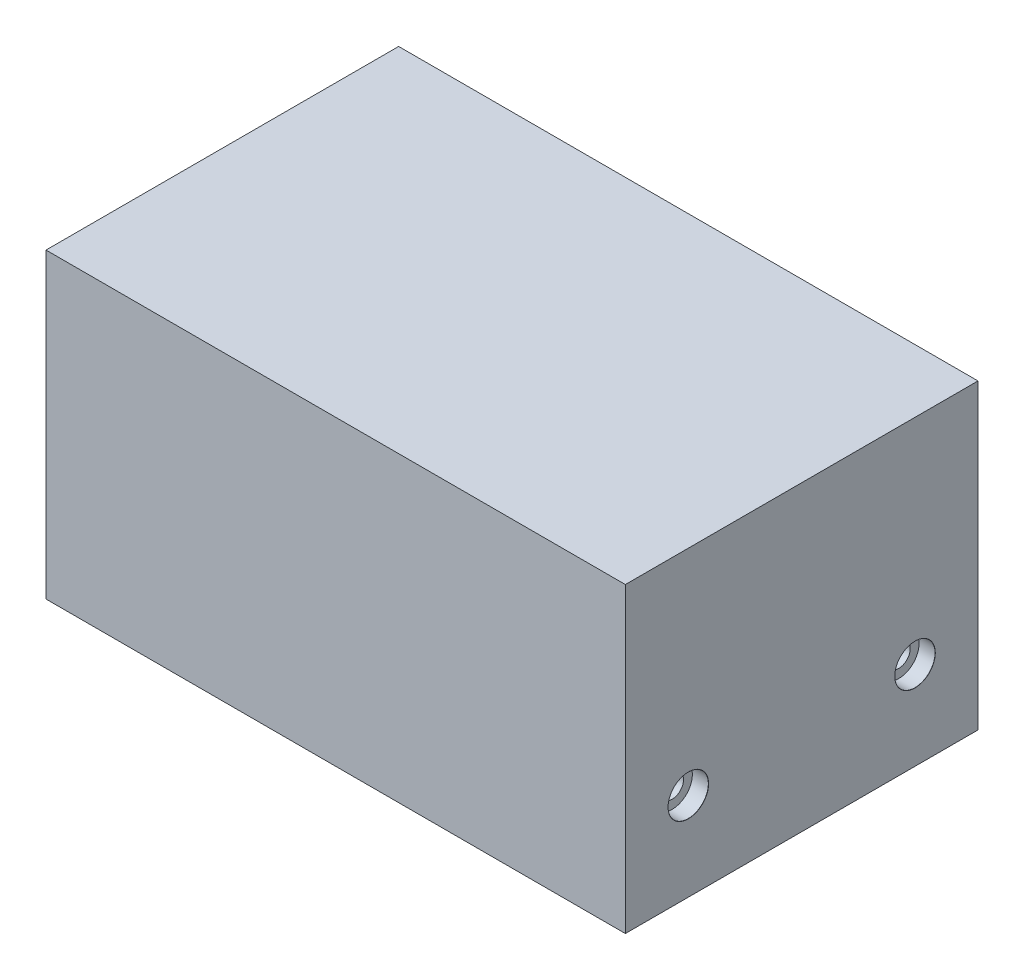
SolidWorks part; units mm, degrees
ref_plane "Alzado" through (0, 0, 0) normal (0, 0, 1) x (1, 0, 0)
ref_plane "Planta" through (0, 0, 0) normal (0, 1, 0) x (1, 0, 0)
ref_plane "Vista lateral" through (0, 0, 0) normal (1, 0, 0) x (0, 0, -1)
sketch "Croquis1" plane through (0, 0, 0) normal (0, 1, 0) x (1, 0, 0)
  line L1 (0, 0) -> (115, 0)
  line L2 (0, 0) -> (0, 70)
  line L3 (0, 70) -> (115, 70)
  line L4 (115, 0) -> (115, 70)
  dimension "D1" = 115
  dimension "D2" = 70
extrude "Saliente-Extruir1" add sketch "Croquis1" along normal blind 5
sketch "Croquis2" plane through (0, 5, 0) normal (0, 1, 0) x (1, 0, 0)
  line L0 (0, 0) -> (115, 0)
  line L1 (115, 0) -> (115, 70)
  line L2 (115, 70) -> (0, 70)
  line L3 (0, 70) -> (0, 65)
  line L4 (0, 70) -> (0, 0) construction
  line L5 (0, 65) -> (110, 65)
  line L6 (110, 65) -> (110, 5)
  line L7 (110, 5) -> (0, 5)
  line L8 (0, 5) -> (0, 0)
  dimension "D1" = 5
  dimension "D2" = 5
  dimension "D3" = 5
extrude "Saliente-Extruir2" add sketch "Croquis2" along normal blind 55
sketch "Croquis3" plane through (110, 0, 0) normal (-1, 0, 0) x (0, 0, 1)
  line L0 (-65, 60) -> (-65, 55)
  line L1 (-65, 60) -> (-65, 5) construction
  line L2 (-65, 55) -> (-5, 55)
  line L3 (-5, 60) -> (-5, 5) construction
  line L4 (-5, 55) -> (-5, 60)
  line L5 (-5, 60) -> (-65, 60)
  dimension "D1" = 5
extrude "Saliente-Extruir3" add sketch "Croquis3" along normal blind 110
sketch "Croquis4" plane through (110, 0, 0) normal (-1, 0, 0) x (0, 0, 1)
  line L0 (-65, 5) -> (-65, 10) construction
  line L1 (-65, 55) -> (-65, 5) construction
  line L2 (-5, 55) -> (-5, 5) construction
  line L3 (-65, 10) -> (-50, 10)
  line L4 (-65, 10) -> (-65, 25)
  line L5 (-65, 25) -> (-50, 25)
  line L6 (-50, 10) -> (-50, 25)
  line L7 (-5, 10) -> (-20, 10)
  line L8 (-5, 10) -> (-5, 25)
  line L9 (-5, 25) -> (-20, 25)
  line L10 (-20, 10) -> (-20, 25)
  line L11 (-65, 5) -> (-5, 5) construction
  dimension "D1" = 5
  dimension "D2" = 15
  dimension "D3" = 15
  dimension "D4" = 15
  dimension "D5" = 15
  dimension "D6" = 5
extrude "Saliente-Extruir4" add sketch "Croquis4" along normal blind 5
sketch "Croquis5" plane through (115, 0, 0) normal (1, 0, 0) x (0, 0, -1)
  line L0 (0, 0) -> (0, 17.5) construction
  line L1 (0, 60) -> (0, 0) construction
  line L2 (0, 17.5) -> (70, 17.5) construction
  line L3 (70, 60) -> (70, 0) construction
  line L4 (0, 17.5) -> (12.5, 17.5) construction
  point P5 (57.5, 17.5)
  point P10 (12.5, 17.5)
  dimension "D1" = 17.5
  dimension "D2" = 12.5
  dimension "D3" = 12.5
hole_wizard "Refrentado para tornillo con cabeza hueca de M41" positions "Croquis6" profile "Croquis7" counterbore size "M4" standard "DIN"
sketch "Croquis6" plane through (115, 0, 0) normal (1, 0, 0) x (0, 0, -1)
  point P0 (12.5, 17.5)
  point P3 (57.5, 17.5)
sketch "Croquis7" plane through (115, 17.5, -12.5) normal (0, 1, 0) x (0, 0, -1)
  line L0 (0, 0) -> (0, 21.8519)
  line L1 (0, 21.8519) -> (2.25, 20.5)
  line L2 (2.25, 20.5) -> (2.25, 3.2)
  line L3 (2.25, 3.2) -> (4, 3.2)
  line L5 (4, 3.2) -> (4, 0.025)
  line L6 (4, 0.025) -> (4.025, 0)
  line L7 (4.025, 0) -> (0, 0)
  line L8 (-4, 0.025) -> (-4.025, 0) construction
  line L10 (0, 21.8519) -> (-2.25, 20.5) construction
  line L11 (0, -6.35) -> (0, 107.95) construction
  dimension "Diámetro de taladro" = 4.5
  dimension "Profundidad de taladro" = 20.5
  dimension "Diámetro de refrentado" = 8
  dimension "Profundidad de refrentado" = 3.2
  dimension "Diámetro de avellanado cercano" = 8.05
  dimension "Ángulo de avellanado cercano" = 90
  dimension "Ángulo de perforador" = 118
